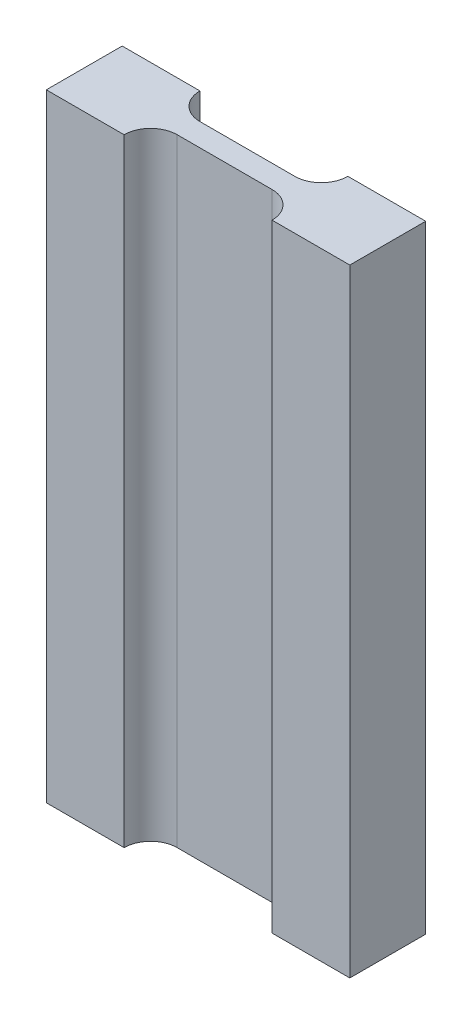
SolidWorks part; units mm, degrees
ref_plane "Front Plane" through (0, 0, 0) normal (0, 0, 1) x (1, 0, 0)
ref_plane "Top Plane" through (0, 0, 0) normal (0, 1, 0) x (1, 0, 0)
ref_plane "Right Plane" through (0, 0, 0) normal (1, 0, 0) x (0, 0, -1)
sketch "Sketch1" plane through (0, 0, 0) normal (0, 1, 0) x (1, 0, 0)
  line L1 (0, 0) -> (4.1, 0)
  line L2 (0, 0) -> (0, 4)
  line L3 (0, 4) -> (4.1, 4)
  line L4 (16, 0) -> (16, 4)
  line L5 (11.9, 0) -> (16, 0)
  line L6 (5.5, 2.6) -> (10.5, 2.6)
  line L7 (11.9, 4) -> (16, 4)
  line L8 (5.5, 1.4) -> (10.5, 1.4)
  arc A0 (10.5, 1.4) -> (11.9, 0) centre (10.5, 0) cw
  arc A1 (5.5, 1.4) -> (4.1, 0) centre (5.5, 0) ccw
  arc A2 (5.5, 2.6) -> (4.1, 4) centre (5.5, 4) cw
  arc A3 (10.5, 2.6) -> (11.9, 4) centre (10.5, 4) ccw
  point P7 (0, 0)
  point P10 (0, 0)
  dimension "D3" = 1.4
  dimension "D4" = 4.1
  dimension "D1" = 5
  dimension "D2" = 4
  dimension "D5" = 1.9799
extrude "Boss-Extrude1" add sketch "Sketch1" along normal blind 32.55
